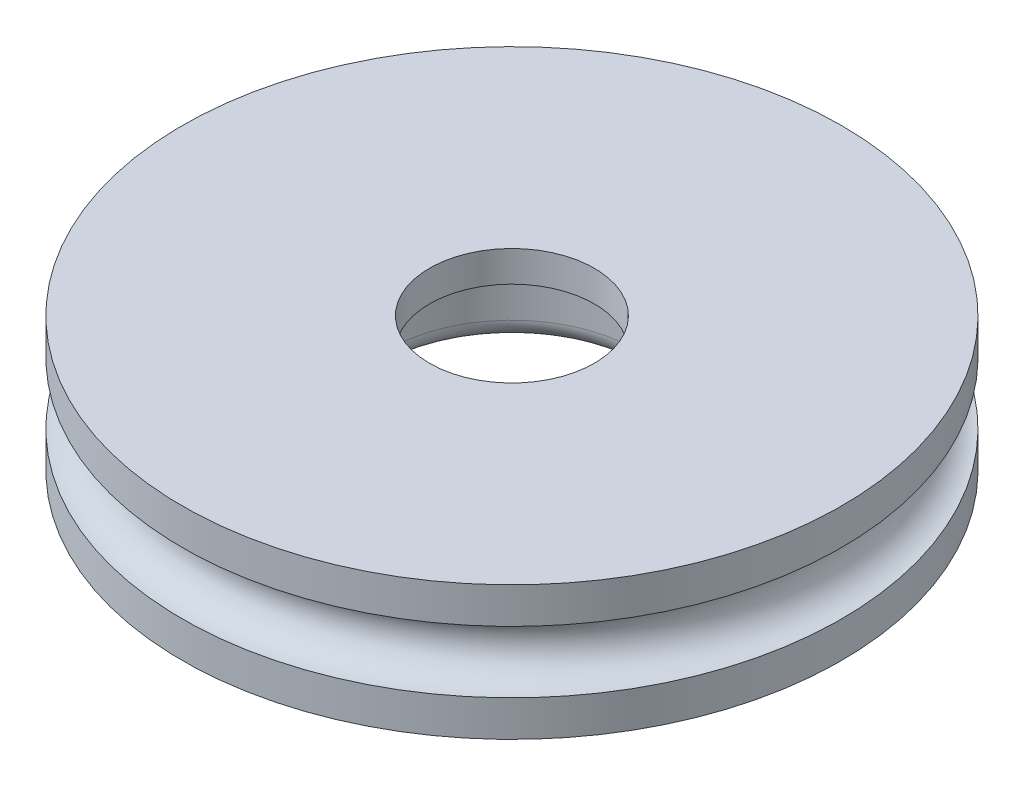
SolidWorks part; units mm, degrees
ref_plane "Front Plane" through (0, 0, 0) normal (0, 0, 1) x (1, 0, 0)
ref_plane "Top Plane" through (0, 0, 0) normal (0, 1, 0) x (1, 0, 0)
ref_plane "Right Plane" through (0, 0, 0) normal (1, 0, 0) x (0, 0, -1)
sketch "Sketch1" plane through (0, 0, 0) normal (0, 1, 0) x (1, 0, 0)
  circle A2 centre (0, 0) radius 3.05
  circle A3 centre (0, 0) radius 8
  dimension "D1" = 6.1
  dimension "D2" = 16
extrude "Boss-Extrude1" add sketch "Sketch1" along normal mid plane 3.25
sketch "Sketch2" plane through (0, 0, 0) normal (1, 0, 0) x (0, 0, -1)
  line L0 (-8, -1.625) -> (-8, -0.75) construction
  line L1 (-8, 1.625) -> (-8, -1.625) construction
  line L2 (-8, 1.625) -> (-8, 0.75) construction
  line L3 (-8, 0.75) -> (-8, -0.75)
  line L4 (-8, -1.625) -> (8, -1.625) construction
  arc A0 (-8, 0.75) -> (-8, -0.75) centre (-8, 0) cw
  dimension "D1" = 1.5
  dimension "D2" = 0.75
  dimension "D3" = 0.875
revolve "Cut-Revolve1" cut sketch "Sketch2" angle 360 about axis through (0, 1.625, 0) along (0, -1, 0)
sketch "Sketch3" plane through (0, 1.625, 0) normal (0, 1, 0) x (1, 0, 0)
  circle A0 centre (0, 0) radius 3.5
  circle A1 centre (0, 0) radius 2
  dimension "D1" = 4
  dimension "D2" = 7
extrude "Boss-Extrude2" add sketch "Sketch3" against normal blind 0.75
sketch "Sketch4" plane through (0, -1.625, 0) normal (0, -1, 0) x (1, 0, 0)
  circle A0 centre (0, 0) radius 6.5
  circle A1 centre (0, 0) radius 8 construction
  circle A2 centre (0, 0) radius 3
  dimension "D1" = 1.5
  dimension "D2" = 6
extrude "Cut-Extrude1" cut sketch "Sketch4" against normal blind 0.5
fillet "Fillet1" radius 0.5 2 edges at (0, -1.125, -3.05) (0, 0.875, 3.05)
